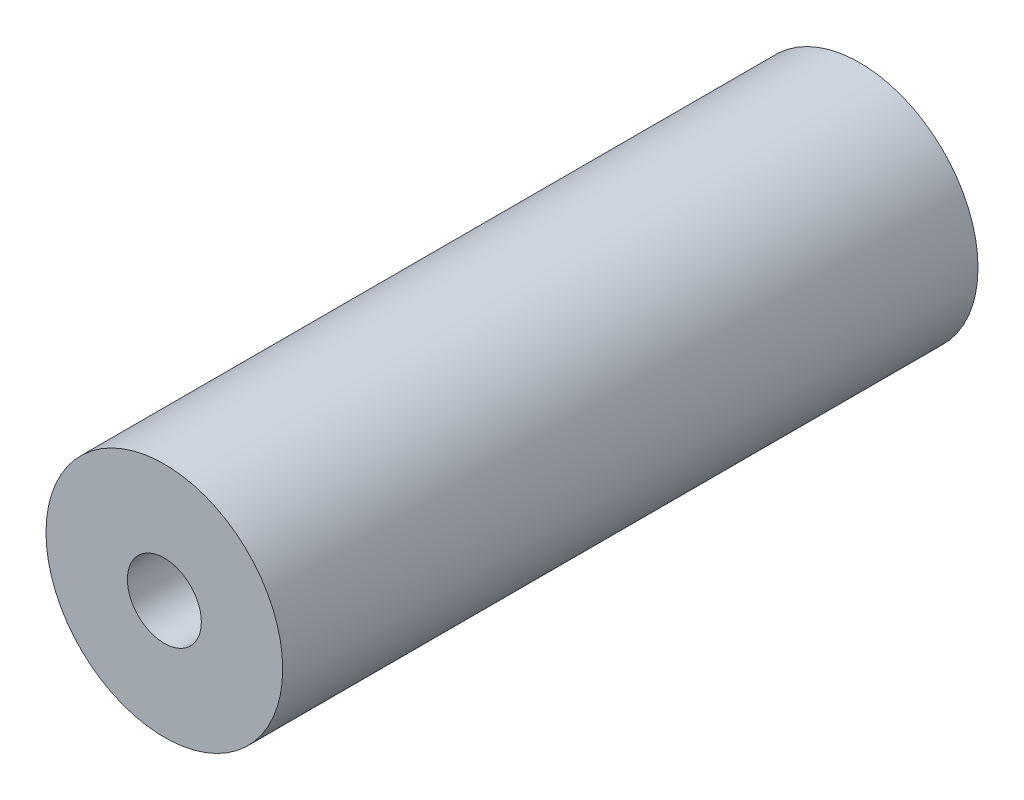
SolidWorks part; units mm, degrees
material "ASTM A36 Steel"
ref_plane "Front Plane" through (0, 0, 0) normal (0, 0, 1) x (1, 0, 0)
ref_plane "Top Plane" through (0, 0, 0) normal (0, 1, 0) x (1, 0, 0)
ref_plane "Right Plane" through (0, 0, 0) normal (1, 0, 0) x (0, 0, -1)
sketch "Sketch1" plane through (0, 0, 0) normal (1, 0, 0) x (0, 0, -1)
  line L4 (0, 0.8128) -> (4.7752, 0.8128)
  line L5 (4.7752, 0.8128) -> (4.7752, 0.254)
  line L6 (4.7752, 0.254) -> (0, 0.254)
  line L7 (0, 0.254) -> (0, 0.8128)
  line L8 (4.7752, 0) -> (4.8263, 0) construction
  dimension "D1" = 1.6256
  dimension "D2" = 0.508
  dimension "D3" = 4.7752
revolve "Revolve1" add sketch "Sketch1" angle 360 about L8
